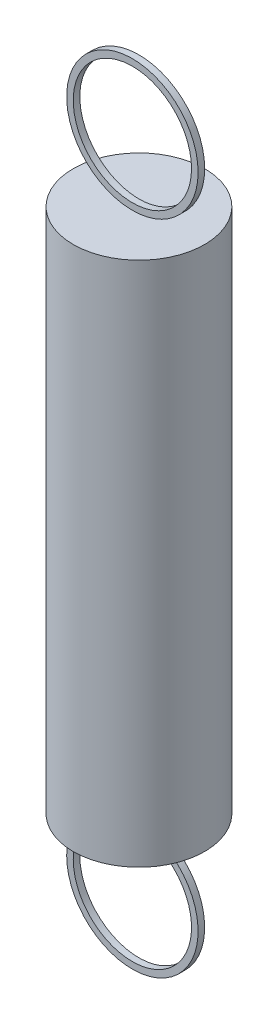
SolidWorks part; units mm, degrees
ref_plane "Front Plane" through (0, 0, 0) normal (0, 0, 1) x (1, 0, 0)
ref_plane "Top Plane" through (0, 0, 0) normal (0, 1, 0) x (1, 0, 0)
ref_plane "Right Plane" through (0, 0, 0) normal (1, 0, 0) x (0, 0, -1)
sketch "Sketch1" plane through (0, 0, 0) normal (0, 1, 0) x (1, 0, 0)
  circle A0 centre (0, 0) radius 5
  dimension "D1" = 10
extrude "Boss-Extrude1" add sketch "Sketch1" along normal blind 40 contours A0
sketch "Sketch3" plane through (0, 0, 0) normal (0, 0, 1) x (1, 0, 0)
  line L1 (5, 40) -> (-5, 40) construction
  line L2 (-5, 20) -> (5, 20) construction
  line L3 (-5, 40) -> (-5, 0) construction
  line L4 (5, 0) -> (5, 40) construction
  circle A0 centre (0, 45) radius 5
  circle A1 centre (0, 45) radius 4.5
  circle A2 centre (0, -5) radius 4.5
  circle A3 centre (0, -5) radius 5
  dimension "D1" = 0.5
  dimension "D2" = 10
extrude "Boss-Extrude2" add sketch "Sketch3" along normal blind 0.5 separate body
